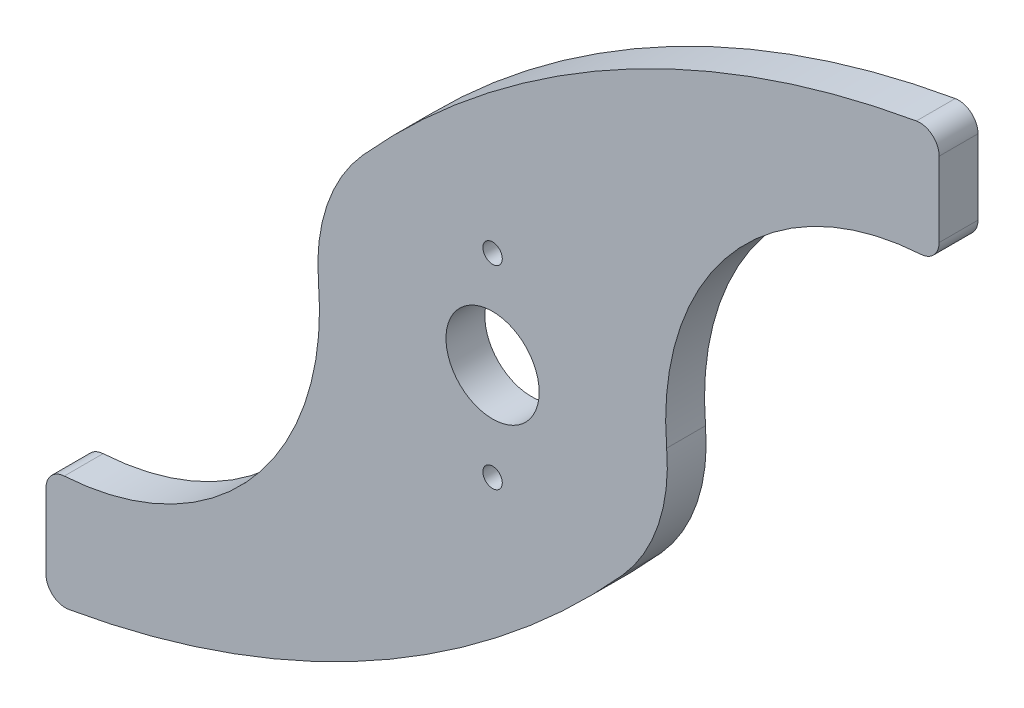
SolidWorks part; units mm, degrees
material "Alloy Steel"
ref_plane "Front Plane" through (0, 0, 0) normal (0, 0, 1) x (1, 0, 0)
ref_plane "Top Plane" through (0, 0, 0) normal (0, 1, 0) x (1, 0, 0)
ref_plane "Right Plane" through (0, 0, 0) normal (1, 0, 0) x (0, 0, -1)
sketch "Sketch1" plane through (0, 0, 0) normal (0, 0, 1) x (1, 0, 0)
  circle A0 centre (0, 0) radius 45
  circle A1 centre (0, 0) radius 12
  dimension "D1" = 24
  dimension "D2" = 90
extrude "Boss-Extrude1" add sketch "Sketch1" along normal blind 10
sketch "Sketch2" plane through (0, 0, 10) normal (0, 0, 1) x (1, 0, 0)
  line L0 (115, 110) -> (115, 80)
  line L1 (-59.3023, 35.6577) -> (81.0786, -48.7514) construction
  line L2 (-115, -110) -> (-115, -80)
  arc A0 (-33.4362, 30.1168) -> (115, 110) centre (152.3205, -137.1987) cw
  circle A1 centre (0, 0) radius 45 construction
  arc A2 (115, 80) -> (44.8295, 3.9136) centre (114.5643, 10.0014) ccw
  arc A3 (44.8295, 3.9136) -> (-33.4362, 30.1168) centre (0, 0) ccw
  arc A4 (33.4362, -30.1168) -> (-115, -110) centre (-152.3205, 137.1987) cw
  arc A5 (-115, -80) -> (-44.8295, -3.9136) centre (-114.5643, -10.0014) ccw
  arc A6 (44.8295, 3.9136) -> (38.5653, -23.1888) centre (0, 0) ccw
  arc A7 (-44.8295, -3.9136) -> (33.4362, -30.1168) centre (0, 0) ccw
  circle M2 centre (0, 0) radius 45
  dimension "D1" = 250
  dimension "D2" = 70
  dimension "D6" = 250
  dimension "D7" = 70
  dimension "D3" = 30
  dimension "D4" = 115
  dimension "D5" = 80
  dimension "D8" = 30
  dimension "D9" = 80
  dimension "D10" = 115
extrude "Boss-Extrude3" add sketch "Sketch2" against normal blind 10 contours A5 L2 A4 M2 | A2 L0 A0 M2
fillet "Fillet2" radius 5 4 edges at (-115, -110, 5) (-115, -80, 5) (115, 80, 5) (115, 110, 5)
sketch "Sketch3" plane through (0, 0, 10) normal (0, 0, 1) x (1, 0, 0)
  circle A0 centre (0, 0) radius 25 construction
  circle A1 centre (0, 25) radius 2.5
  circle A2 centre (0, -25) radius 2.5
  dimension "D1" = 50
  dimension "D2" = 5
  dimension "D3" = 5
extrude "Cut-Extrude1" cut sketch "Sketch3" against normal through all
